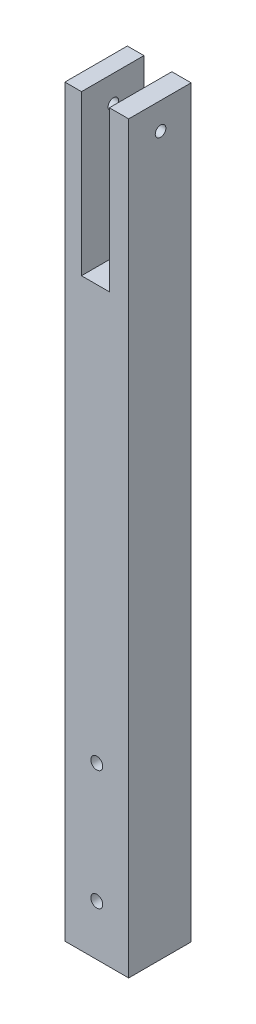
SolidWorks part; units mm, degrees
ref_plane "Front Plane" through (0, 0, 0) normal (1, 0, 0) x (0, 1, 0)
ref_plane "Top Plane" through (0, 0, 0) normal (0, 0, 1) x (0, 1, 0)
ref_plane "Right Plane" through (0, 0, 0) normal (0, 1, 0) x (-1, 0, 0)
sketch "Esquisse1" plane through (0, 0, 0) normal (0, 0, 1) x (0, 1, 0)
  line L1 (-58.5328, 17.7152) -> (221.4672, 17.7152)
  line L2 (-58.5328, 17.7152) -> (-58.5328, -6.2848)
  line L3 (-58.5328, -6.2848) -> (221.4672, -6.2848)
  line L4 (221.4672, 17.7152) -> (221.4672, -6.2848)
  dimension "D1" = 24
  dimension "D2" = 280
extrude "main" add sketch "Esquisse1" along normal blind 24
sketch "Esquisse3" plane through (0, 221.4672, 0) normal (0, 1, 0) x (-1, 0, 0)
  line L0 (-6.2848, 24) -> (17.7152, 24) construction
  line L1 (0.9652, 24) -> (11.4652, 24)
  line L2 (0.9652, 24) -> (0.9652, 0)
  line L3 (0.9652, 0) -> (11.4652, 0)
  line L4 (11.4652, 24) -> (11.4652, 0)
  line L5 (13.2, 0) -> (-13.2, 0) construction
  line L6 (17.7152, 24) -> (17.7152, 0) construction
  dimension "D1" = 10.5
  dimension "D2" = 6.25
extrude "fourche" cut sketch "Esquisse3" against normal blind 60
sketch "Esquisse5" plane through (-17.7152, 0, 0) normal (-1, 0, 0) x (0, -1, 0)
  line L0 (-221.4672, 24) -> (58.5328, 24) construction
  line L1 (-221.4672, 24) -> (-221.4672, 0) construction
  circle A0 centre (-211.4672, 12) radius 2
  dimension "D1" = 4
  dimension "D2" = 12
  dimension "D3" = 10
extrude "trou_fourche" cut sketch "Esquisse5" against normal blind 27 contours A0
sketch "Esquisse6" plane through (0, 0, 0) normal (0, 0, -1) x (1, 0, 0)
  line L0 (-17.7152, 58.5328) -> (6.2848, 58.5328) construction
  line L1 (-17.7152, -221.4672) -> (-17.7152, 58.5328) construction
  circle A0 centre (-5.7152, 39.4828) radius 2.25
  circle A1 centre (-5.7152, -5.5172) radius 2.25
  dimension "D1" = 4.5
  dimension "D4" = 4.5
  dimension "D2" = 19.05
  dimension "D3" = 12
  dimension "D5" = 12
  dimension "D6" = 45
extrude "trou_equerre" cut sketch "Esquisse6" against normal blind 27
chamfer "Chanfrein1" distance 0.5 1 edges at (6.2848, 81.4672, 0)
chamfer "Chanfrein2" distance 0.5 1 edges at (-11.4652, 191.4672, 0)
chamfer "Chanfrein3" distance 0.5 1 edges at (-0.9652, 191.4672, 0)
chamfer "Chanfrein4" distance 0.5 angle 45 1 edges at (-14.8402, 221.4672, 0)
chamfer "Chanfrein5" distance 0.5 1 edges at (2.6598, 221.4672, 0)
chamfer "Chanfrein6" distance 0.5 1 edges at (-6.2152, 161.4672, 0)
chamfer "Chanfrein7" distance 0.5 1 edges at (-17.7152, 81.2172, 0)
chamfer "Chanfrein8" distance 0.3 angle 45 1 edges at (-7.9652, 5.5172, 0)
chamfer "Chanfrein9" distance 0.3 angle 45 1 edges at (-7.9652, -39.4828, 0)
chamfer "Chanfrein11" distance 0.5 1 edges at (-5.7152, -58.5328, 0)
equation "\"D2@Esquisse6\"=16.8+2.25"
